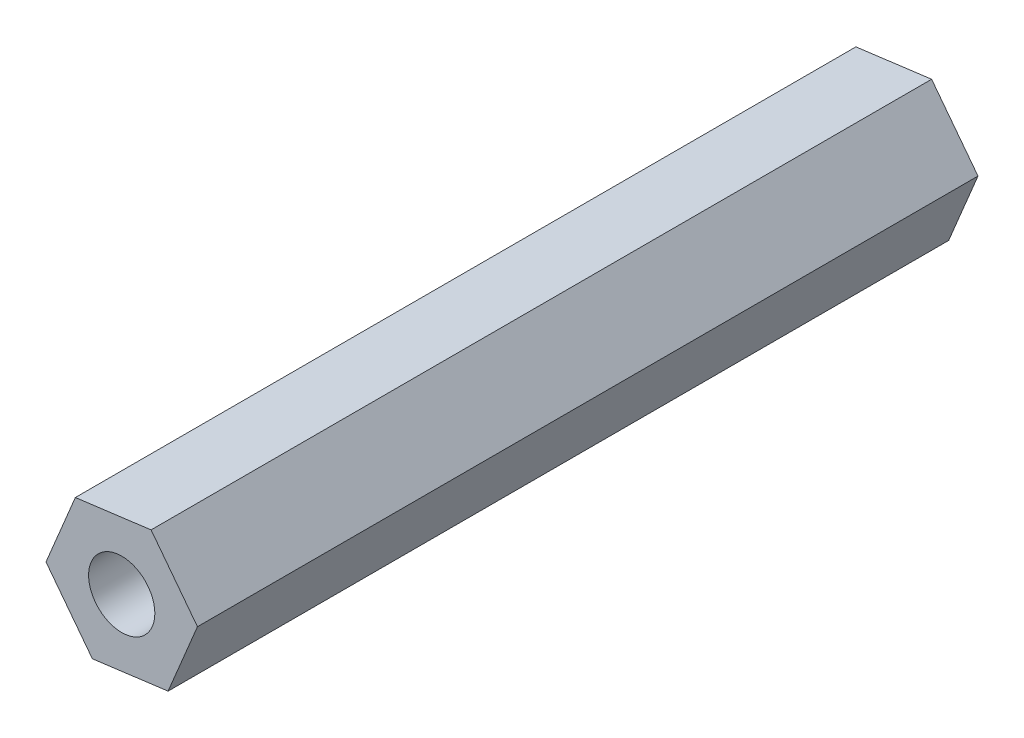
SolidWorks part; units mm, degrees
ref_plane "Front Plane" through (0, 0, 0) normal (0, 0, 1) x (1, 0, 0)
ref_plane "Top Plane" through (0, 0, 0) normal (0, 1, 0) x (1, 0, 0)
ref_plane "Right Plane" through (0, 0, 0) normal (1, 0, 0) x (0, 0, -1)
sketch "Sketch1" plane through (0, 0, 0) normal (0, 0, 1) x (1, 0, 0)
  line L1 (7.2715, 0.9426) -> (2.8194, 6.7686)
  line L2 (2.8194, 6.7686) -> (-4.4521, 5.826)
  line L3 (-4.4521, 5.826) -> (-7.2715, -0.9426)
  line L4 (-7.2715, -0.9426) -> (-2.8194, -6.7686)
  line L5 (-2.8194, -6.7686) -> (4.4521, -5.826)
  line L6 (4.4521, -5.826) -> (7.2715, 0.9426)
  circle A0 centre (0, 0) radius 6.35 construction
  circle A1 centre (0, 0) radius 3.18
extrude "Boss-Extrude1" add sketch "Sketch1" along normal blind 74.95
move or copy body "Body-Move/Copy1" [suppressed] bodies to move or copy 101
